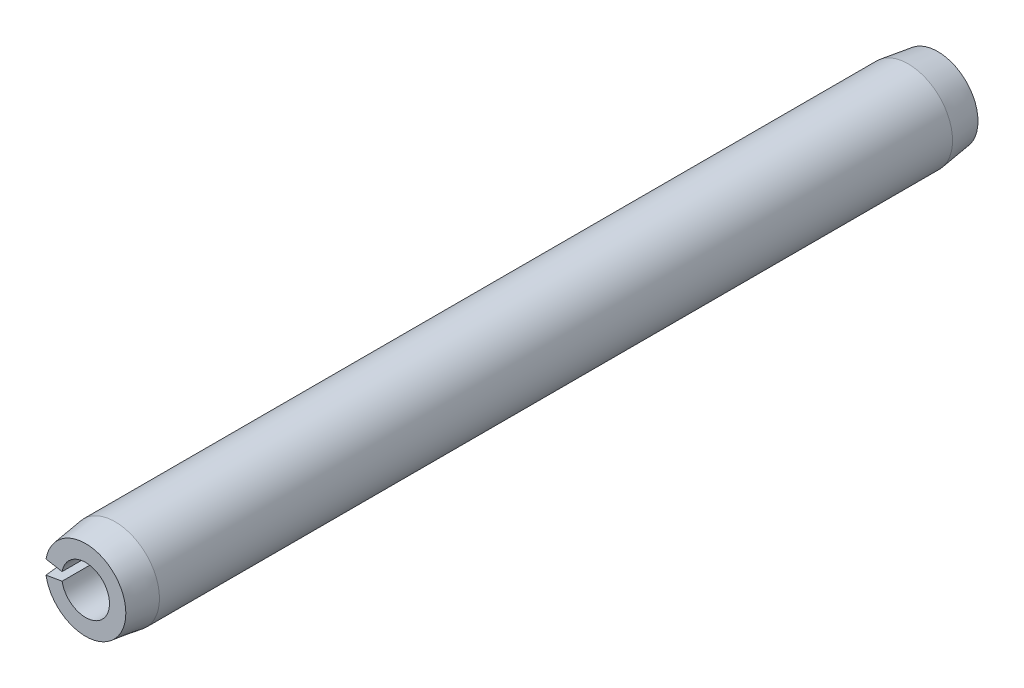
SolidWorks part; units mm, degrees
ref_plane "Front Plane" through (0, 0, 0) normal (0, 0, 1) x (1, 0, 0)
ref_plane "Top Plane" through (0, 0, 0) normal (0, 1, 0) x (1, 0, 0)
ref_plane "Right Plane" through (0, 0, 0) normal (1, 0, 0) x (0, 0, -1)
sketch "Sketch5" plane through (0, 0, 0) normal (0, 0, 1) x (1, 0, 0)
  line L0 (0.5334, 0) -> (0.9906, 0) construction
  line L1 (-0.9756, 0.172) -> (-0.5253, 0.0926)
  line L2 (-0.5253, -0.0926) -> (-0.9756, -0.172)
  arc A0 (-0.9756, -0.172) -> (-0.9756, 0.172) centre (0, 0) ccw
  arc A1 (-0.5253, -0.0926) -> (-0.5253, 0.0926) centre (0, 0) ccw
  circle A2 centre (0, 0) radius 0.9906 construction
  dimension "Diameter" = 1.9812
  dimension "Wall Thickness" = 0.4572
  dimension "Opening Angle" = 20
sketch "Sketch6" plane through (0, 0, 0) normal (1, 0, 0) x (0, 0, -1)
  line L0 (9.525, 0) -> (-9.525, 0) construction
  line L1 (0, 0.9906) -> (0, -0.9906) construction
  line L4 (0, 0.9906) -> (0, -0.9906) construction
  line L5 (9.525, 0) -> (9.525, 0.9906) construction
  line L6 (9.525, 0.9906) -> (-9.525, 0.9906) construction
  line L7 (-9.525, 0.9906) -> (-9.525, 0) construction
  line L8 (9.525, 0.8992) -> (8.8646, 0.9906)
  dimension "Length" = 19.05
  dimension "Chamfer" = 0.6604
  dimension "D1" = 0.0914
sketch "Sketch1" plane through (0, 0, 0) normal (0, 0, 1) x (1, 0, 0)
  line L1 (-0.5253, -0.0926) -> (-0.9756, -0.172) construction
  line L2 (-0.9756, 0.172) -> (-0.5253, 0.0926) construction
  line L3 (-0.5253, -0.0926) -> (-0.9756, -0.172)
  line L4 (-0.9756, 0.172) -> (-0.5253, 0.0926)
  arc A2 (-0.9756, -0.172) -> (-0.9756, 0.172) centre (0, 0) ccw construction
  arc A3 (-0.5253, -0.0926) -> (-0.5253, 0.0926) centre (0, 0) ccw construction
  arc A4 (-0.9756, -0.172) -> (-0.9756, 0.172) centre (0, 0) ccw
  arc A5 (-0.5253, -0.0926) -> (-0.5253, 0.0926) centre (0, 0) ccw
extrude "Extrude1" add sketch "Sketch1" against normal up to vertex (9.525 mm away) and the other way up to vertex (9.525 mm away) up to point (0, 0.9906, -9.525) other way up to point (0, 0.9906, 9.525)
sketch "Sketch2" plane through (0, 0, 0) normal (1, 0, 0) x (0, 0, -1)
  line L0 (9.525, 0.8992) -> (8.8646, 0.9906)
  line L1 (8.8646, 0.9906) -> (9.525, 0.9906)
  line L4 (9.525, 0.9906) -> (9.525, 0.8992)
revolve "Cut-Revolve1" cut sketch "Sketch2" angle 360 about L0
mirror "Mirror1" about plane through (0, 0, 0) normal (0, 0, 1) of "Cut-Revolve1"
equation "\"D1@Sketch6\"=\"Wall Thickness@Sketch5\"*.2"
equation "\"Chamfer@Sketch6\"=\"Diameter@Sketch5\"/3"
